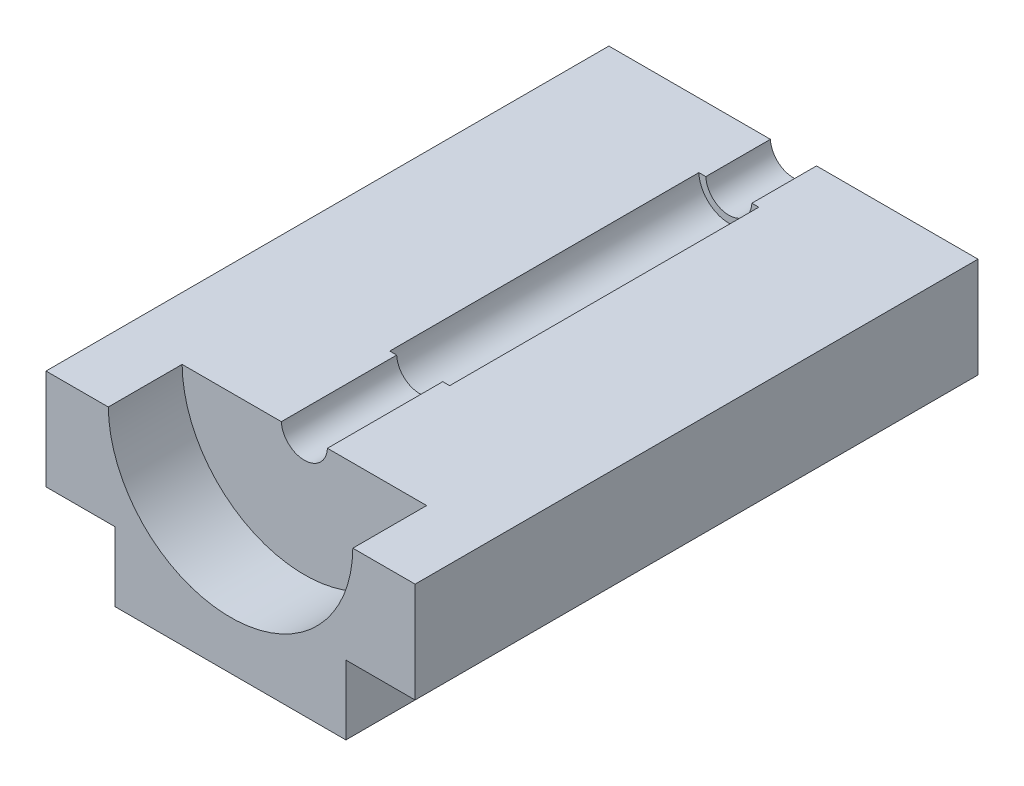
SolidWorks part; units mm, degrees
ref_plane "Front Plane" through (0, 0, 0) normal (0, 0, 1) x (1, 0, 0)
ref_plane "Top Plane" through (0, 0, 0) normal (0, 1, 0) x (1, 0, 0)
ref_plane "Right Plane" through (0, 0, 0) normal (1, 0, 0) x (0, 0, -1)
sketch "Sketch2" plane through (0, 0, 0) normal (0, 0, 1) x (1, 0, 0)
  line L5 (-35, 60) -> (-35, 50)
  line L6 (-52.5, -67.5) -> (52.5, -67.5)
  line L24 (-60, -60) -> (-60, 35)
  line L25 (-27.5, 67.5) -> (27.5, 67.5)
  line L26 (60, -60) -> (60, 35)
  line L27 (0, -100) -> (0, 100) construction
  line L28 (-100, 0) -> (100, 0) construction
  line L29 (-42.5, 42.5) -> (-52.5, 42.5)
  line L34 (35, 60) -> (35, 50)
  line L35 (42.5, 42.5) -> (52.5, 42.5)
  arc A12 (-60, 35) -> (-52.5, 42.5) centre (-52.5, 35) cw
  arc A19 (60, 35) -> (52.5, 42.5) centre (52.5, 35) ccw
  arc A20 (42.5, 42.5) -> (35, 50) centre (42.5, 50) cw
  arc A21 (35, 60) -> (27.5, 67.5) centre (27.5, 60) ccw
  arc A22 (-27.5, 67.5) -> (-35, 60) centre (-27.5, 60) ccw
  arc A23 (-42.5, 42.5) -> (-35, 50) centre (-42.5, 50) ccw
  arc A24 (-60, -60) -> (-52.5, -67.5) centre (-52.5, -60) ccw
  arc A25 (60, -60) -> (52.5, -67.5) centre (52.5, -60) cw
  point P0 (0, 0)
  point P39 (-35, 67.5)
  dimension "D5" = 25
  dimension "D6" = 60
  dimension "D7" = 7.5
  dimension "D2" = 25
  dimension "D3" = 135
  dimension "D8" = 7.5
  dimension "D1" = 67.5
  dimension "D4" = 60
extrude "Boss-Extrude1" add sketch "Sketch2" against normal blind 8
sketch "Sketch3" plane through (0, 0, 0) normal (0, 0, 1) x (1, 0, 0)
  line L0 (0, 100) -> (0, -100) construction
  circle A0 centre (0, -20) radius 13.75
  dimension "D1" = 27.5
  dimension "D2" = 20
extrude "Cut-Extrude1" cut sketch "Sketch3" against normal up to surface (8 mm away) up to face at (0, 21.25, -8)
sketch "Sketch4" plane through (0, 0, -8) normal (0, 0, -1) x (-1, 0, 0)
  line L3 (-40, -57) -> (-40, -20)
  line L4 (0, 100) -> (0, -100) construction
  line L6 (-40, -20) -> (40, -20)
  line L7 (-40, -57) -> (40, -57)
  line L8 (52.5, -67.5) -> (-52.5, -67.5) construction
  line L10 (40, -57) -> (40, -20)
  point P16 (0, -57)
  point P17 (0, -20)
  dimension "D1" = 10.5
  dimension "D3" = 40
  dimension "D4" = 37
extrude "Boss-Extrude2" add sketch "Sketch4" along normal blind 122
sketch "Sketch5" plane through (0, 0, -8) normal (0, 0, -1) x (-1, 0, 0)
  circle A0 centre (0, -20) radius 26.5
  arc A1 (13.75, -20) -> (-13.75, -20) centre (0, -20) ccw construction
  dimension "D1" = 53
extrude "Cut-Extrude2" cut sketch "Sketch5" along normal blind 16
sketch "Sketch6" plane through (0, 0, -8) normal (0, 0, -1) x (-1, 0, 0)
  circle A0 centre (0, -20) radius 6.5
  circle A1 centre (0, -20) radius 13.75 construction
  dimension "D1" = 13
extrude "Cut-Extrude3" cut sketch "Sketch6" along normal up to surface (122 mm away) up to face at (0, -38.5, -130)
sketch "Sketch8" plane through (0, 0, -8) normal (0, 0, -1) x (-1, 0, 0)
  line L1 (-6.5, -20) -> (-5, -20)
  line L2 (5, -20) -> (6.5, -20)
  arc A0 (-5, -20) -> (5, -20) centre (0, -20) ccw
  circle A1 centre (0, -20) radius 13.75 construction
  arc A2 (-6.5, -20) -> (6.5, -20) centre (0, -20) ccw
  arc A3 (-6.5, -20) -> (6.5, -20) centre (0, -20) ccw construction
  dimension "D1" = 10
extrude "Boss-Extrude3" add sketch "Sketch8" along normal blind 25 from surface at 16 starting at face at (0, -28.25, -24)
sketch "Sketch9" plane through (0, 0, -8) normal (0, 0, -1) x (-1, 0, 0)
  line L0 (-6.5, -20) -> (-5, -20)
  line L1 (5, -20) -> (6.5, -20)
  arc A0 (-5, -20) -> (5, -20) centre (0, -20) ccw
  arc A2 (-6.5, -20) -> (6.5, -20) centre (0, -20) ccw
  dimension "D1" = 10
extrude "Boss-Extrude4" add sketch "Sketch9" against normal blind 14 from surface at 122 starting at face at (0, -33.4167, -130)
sketch "Sketch10" plane through (0, 0, 0) normal (0, 0, 1) x (1, 0, 0)
  line L1 (-75, -87.5) -> (75, -87.5)
  line L2 (-75, -87.5) -> (-75, 87.5)
  line L3 (-75, 87.5) -> (75, 87.5)
  line L4 (75, -87.5) -> (75, 87.5)
  line L5 (-75, -87.5) -> (75, 87.5) construction
  line L6 (-75, 87.5) -> (75, -87.5) construction
  point P0 (0, 0)
  dimension "D1" = 150
  dimension "D2" = 175
extrude "Cut-Extrude4" cut sketch "Sketch10" against normal up to surface (8 mm away) up to face at (0, -36.75, -8)
sketch "Sketch12" plane through (0, 0, -8) normal (0, 0, 1) x (1, 0, 0)
  line L0 (-40, -20) -> (-40, -20.25)
  line L1 (-40, -20.25) -> (40, -20.25)
  line L2 (40, -20.25) -> (40, -20)
  line L3 (40, -20) -> (-40, -20)
  line L4 (-40, -57) -> (-40, -20) construction
  line L5 (40, -20) -> (40, -57) construction
  line L6 (5, -20) -> (26.5, -20) construction
  dimension "D1" = 0.25
extrude "Cut-Extrude5" cut sketch "Sketch12" against normal through all both and the other way through all
sketch "Sketch13" plane through (0, 0, -130) normal (0, 0, -1) x (-1, 0, 0)
  line L0 (40, -57) -> (40, -42)
  line L1 (40, -57) -> (40, -20.25) construction
  line L2 (40, -42) -> (25, -42)
  line L3 (25, -42) -> (25, -57)
  line L4 (-40, -57) -> (40, -57) construction
  line L5 (25, -57) -> (40, -57)
  line L6 (0, -115.1141) -> (0, 69.242) construction
  line L7 (-25, -57) -> (-40, -57)
  line L8 (-25, -42) -> (-25, -57)
  line L9 (-40, -42) -> (-25, -42)
  line L10 (-40, -57) -> (-40, -42)
  dimension "D1" = 15
  dimension "D2" = 15
extrude "Cut-Extrude6" cut sketch "Sketch13" against normal up to surface (122 mm away) up to face at (0, -36.875, -8)
